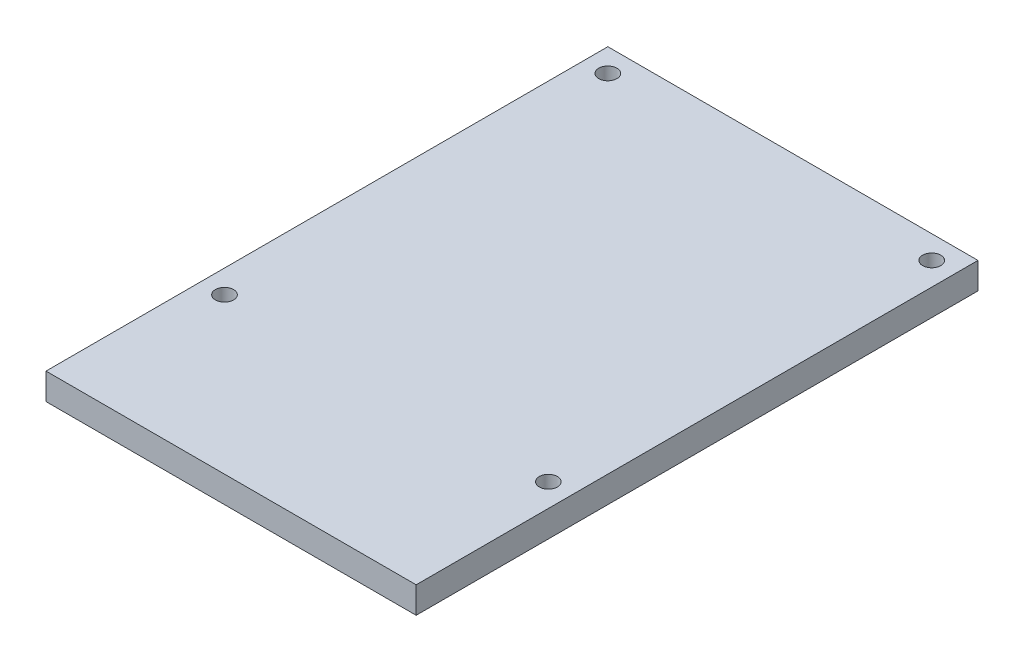
SolidWorks part; units mm, degrees
ref_plane "Front" through (0, 0, 0) normal (0, 0, 1) x (1, 0, 0)
ref_plane "Top" through (0, 0, 0) normal (0, 1, 0) x (1, 0, 0)
ref_plane "Right" through (0, 0, 0) normal (1, 0, 0) x (0, 0, -1)
sketch "Sketch1" plane through (0, 0, 0) normal (0, 1, 0) x (1, 0, 0)
  line L1 (0, 0) -> (56, 0)
  line L2 (0, 0) -> (0, 85)
  line L3 (0, 85) -> (56, 85)
  line L4 (56, 0) -> (56, 85)
  dimension "D1" = 85
  dimension "D2" = 56
extrude "Boss-Extrude1" add sketch "Sketch1" along normal blind 4
sketch "Sketch2" plane through (0, 4, 0) normal (0, 1, 0) x (1, 0, 0)
  line L0 (56, 85) -> (0, 85) construction
  line L1 (0, 85) -> (0, 0) construction
  line L2 (56, 0) -> (56, 85) construction
  circle A0 centre (3.5, 81.5) radius 1.375
  circle A1 centre (52.5, 81.5) radius 1.375
  circle A2 centre (3.5, 23.5) radius 1.375
  circle A3 centre (52.5, 23.5) radius 1.375
  dimension "D9" = 2.75
  dimension "D10" = 2.75
  dimension "D11" = 2.75
  dimension "D12" = 2.75
  dimension "D1" = 3.5
  dimension "D2" = 3.5
  dimension "D3" = 3.5
  dimension "D4" = 3.5
  dimension "D5" = 3.5
  dimension "D6" = 3.5
  dimension "D7" = 58
  dimension "D8" = 58
extrude "Cut-Extrude1" cut sketch "Sketch2" against normal blind 4
